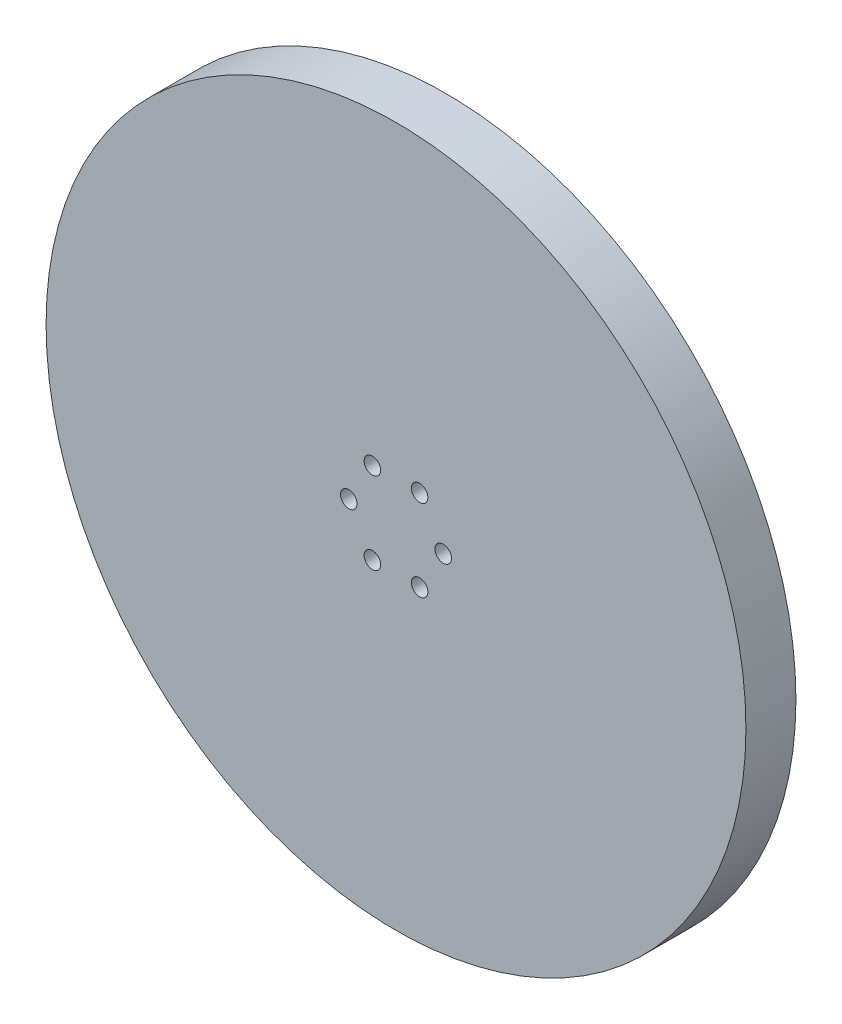
SolidWorks part; units mm, degrees
ref_plane "Front Plane" through (0, 0, 0) normal (0, 0, 1) x (1, 0, 0)
ref_plane "Top Plane" through (0, 0, 0) normal (0, 1, 0) x (1, 0, 0)
ref_plane "Right Plane" through (0, 0, 0) normal (1, 0, 0) x (0, 0, -1)
sketch "Sketch1" plane through (0, 0, 0) normal (0, 0, 1) x (1, 0, 0)
  line L0 (0, 0) -> (-12, 0) construction
  circle A0 centre (0, 0) radius 88.9
  circle A1 centre (-12, 0) radius 2.1
  circle A2 centre (-6, 10.3923) radius 2.1
  circle A3 centre (6, 10.3923) radius 2.1
  circle A4 centre (12, 0) radius 2.1
  circle A5 centre (6, -10.3923) radius 2.1
  circle A6 centre (-6, -10.3923) radius 2.1
  point P5 (-7.1435, -11.851)
  point P6 (0, 0)
  point P18 (0, 0)
  dimension "D1" = 177.8
  dimension "D3" = 4.2
  dimension "D2" = 12
  dimension "D4" = 6
extrude "Boss-Extrude1" add sketch "Sketch1" along normal mid plane 12.7
sketch "Sketch2" plane through (0, 0, -6.35) normal (0, 0, -1) x (-1, 0, 0)
  circle A0 centre (0, 0) radius 57.3
  dimension "D1" = 114.6
extrude "Cut-Extrude1" cut sketch "Sketch2" against normal blind 3 contours A0
